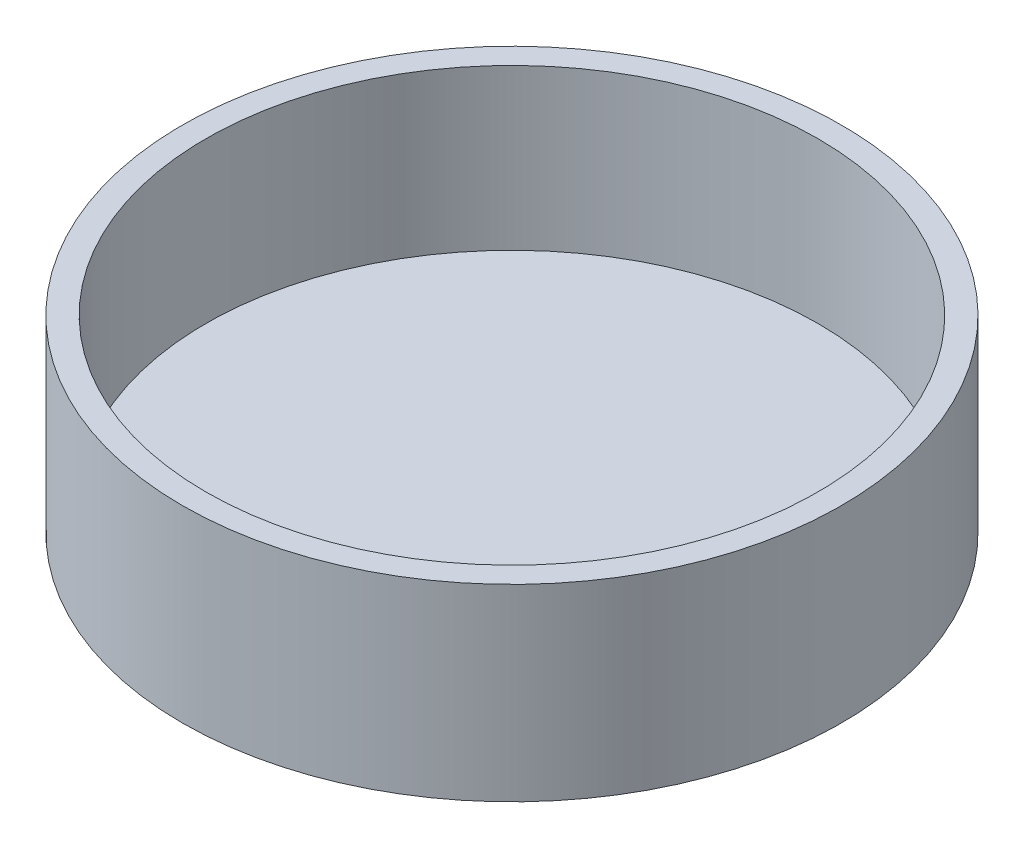
SolidWorks part; units mm, degrees
ref_plane "Front Plane" through (0, 0, 0) normal (0, 0, 1) x (1, 0, 0)
ref_plane "Top Plane" through (0, 0, 0) normal (0, 1, 0) x (1, 0, 0)
ref_plane "Right Plane" through (0, 0, 0) normal (1, 0, 0) x (0, 0, -1)
sketch "Sketch1" plane through (0, 0, 0) normal (0, 1, 0) x (1, 0, 0)
  circle A0 centre (0, 0) radius 32.5
  circle A1 centre (0, 0) radius 35
  point P4 (0, 0)
  point P5 (0, 0)
  dimension "D1" = 65
  dimension "D2" = 70
extrude "Boss-Extrude1" add sketch "Sketch1" against normal blind 20
sketch "Sketch3" plane through (0, -20, 0) normal (0, -1, 0) x (1, 0, 0)
  circle A0 centre (0, 0) radius 32.5
extrude "Boss-Extrude2" add sketch "Sketch3" against normal blind 3
